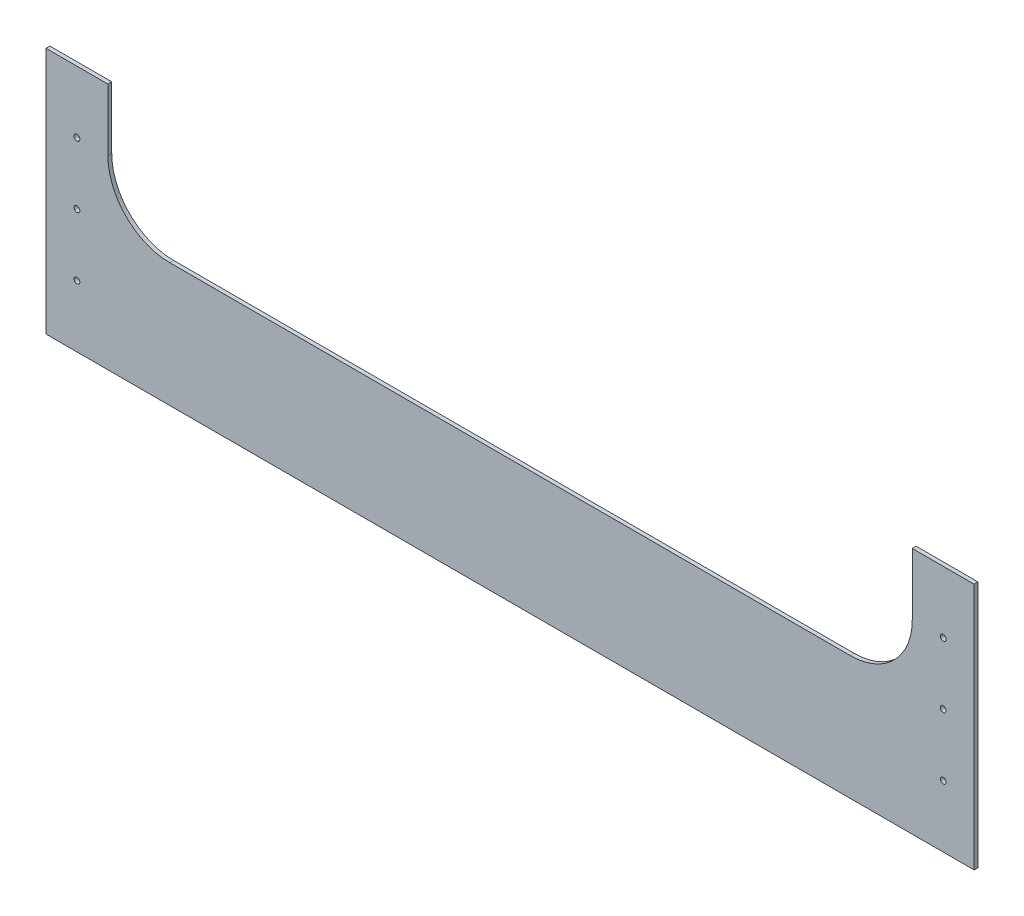
SolidWorks part; units mm, degrees
ref_plane "Front Plane" through (0, 0, 0) normal (0, 0, 1) x (1, 0, 0)
ref_plane "Top Plane" through (0, 0, 0) normal (0, 1, 0) x (1, 0, 0)
ref_plane "Right Plane" through (0, 0, 0) normal (1, 0, 0) x (0, 0, -1)
sketch "Sketch1" plane through (0, 0, 0) normal (0, 0, 1) x (1, 0, 0)
  line L0 (-381, 0) -> (381, 0)
  line L1 (381, 0) -> (381, 203.2)
  line L2 (381, 203.2) -> (330.2, 203.2)
  line L3 (330.2, 203.2) -> (330.2, 152.4)
  line L4 (279.4, 101.6) -> (-279.4, 101.6)
  line L5 (-330.2, 152.4) -> (-330.2, 203.2)
  line L6 (-330.2, 203.2) -> (-381, 203.2)
  line L7 (-381, 203.2) -> (-381, 0)
  line L8 (-355.6, 152.4) -> (355.6, 152.4) construction
  line L9 (-355.6, 152.4) -> (-355.6, 101.6) construction
  arc A0 (330.2, 152.4) -> (279.4, 101.6) centre (279.4, 152.4) cw
  arc A1 (-279.4, 101.6) -> (-330.2, 152.4) centre (-279.4, 152.4) cw
  circle A2 centre (-355.6, 152.4) radius 2.3813
  circle A3 centre (355.6, 152.4) radius 2.3813
  circle A4 centre (355.6, 101.6) radius 2.3813
  circle A5 centre (355.6, 50.8) radius 2.3813
  circle A6 centre (-355.6, 101.6) radius 2.3813
  circle A7 centre (-355.6, 50.8) radius 2.3813
  point P0 (0, 101.6)
  point P4 (0, 0)
  point P12 (355.6, 53.3039)
  dimension "D5" = 50.8
  dimension "D6" = 4.7625
  dimension "D1" = 762
  dimension "D2" = 203.2
  dimension "D3" = 101.6
  dimension "D4" = 50.8
  dimension "D9" = 711.2
  dimension "D10" = 50.8
  dimension "D11" = 50.8
  dimension "D12" = 25.4
  dimension "D7" = 2
  dimension "D8" = 3
extrude "Boss-Extrude1" add sketch "Sketch1" along normal blind 3.175
